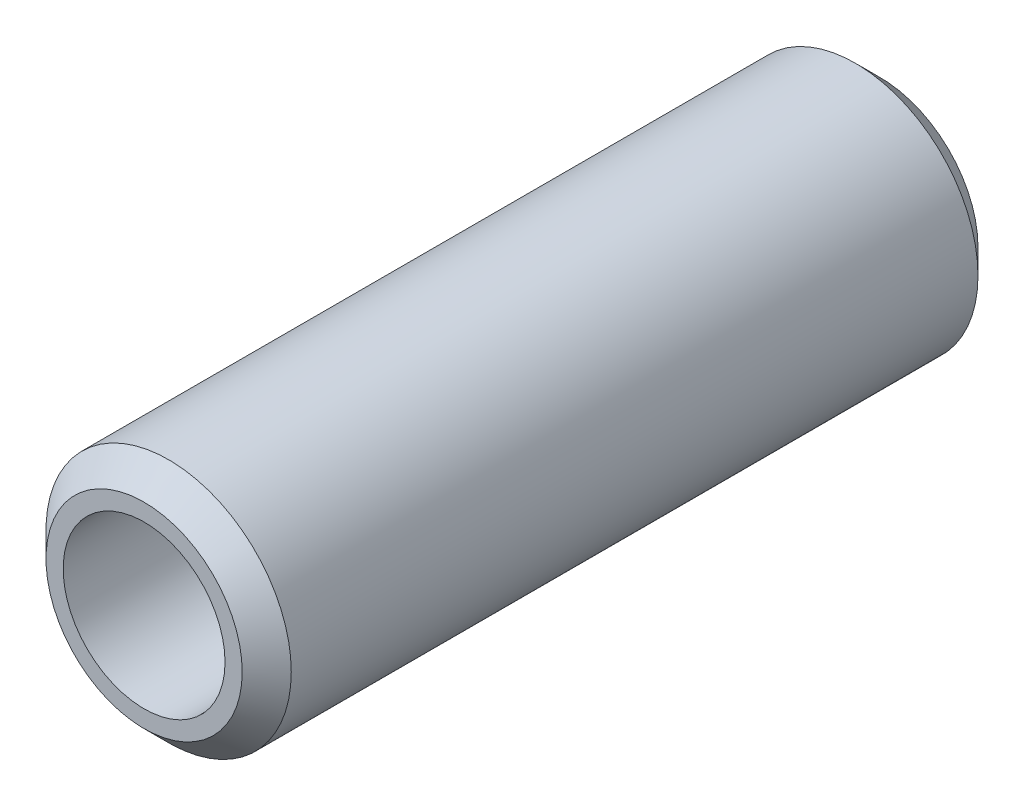
SolidWorks part; units mm, degrees
ref_plane "Plan de face" through (0, 0, 0) normal (0, 0, 1) x (1, 0, 0)
ref_plane "Plan de dessus" through (0, 0, 0) normal (0, 1, 0) x (1, 0, 0)
ref_plane "Plan de droite" through (0, 0, 0) normal (1, 0, 0) x (0, 0, -1)
sketch "Esquisse1" plane through (0, 0, 0) normal (0, 0, 1) x (1, 0, 0)
  circle A0 centre (0, 0) radius 2.5
  dimension "D1" = 5
extrude "Extrusion1" add sketch "Esquisse1" along normal blind 15
chamfer "Chanfrein1" distance 0.5 angle 45 2 edges at (2.5, 0, 0) (2.5, 0, 15)
hole_wizard "Trou taraudé M41" positions "Esquisse3" profile "Esquisse2" tap size "M4" standard "ISO" end condition through all
sketch "Esquisse3" plane through (0, 0, 15) normal (0, 0, 1) x (1, 0, 0)
  point P0 (0, 0)
sketch "Esquisse2" plane through (0, 0, 15) normal (1, 0, 0) x (0, -1, 0)
  line L0 (0, 0) -> (0, 15)
  line L1 (0, 15) -> (1.65, 15)
  line L2 (1.65, 15) -> (1.65, 0)
  line L5 (1.65, 0) -> (0, 0)
  line L11 (0, -6.35) -> (0, 107.95) construction
  dimension "Diamètre du trou pour taraudage jusqu'au prochain" = 3.3
  dimension "Profondeur du trou pour taraudage jusqu'au prochain" = 15
cosmetic thread "Filetage de perçage1" parameters "D2"=4
